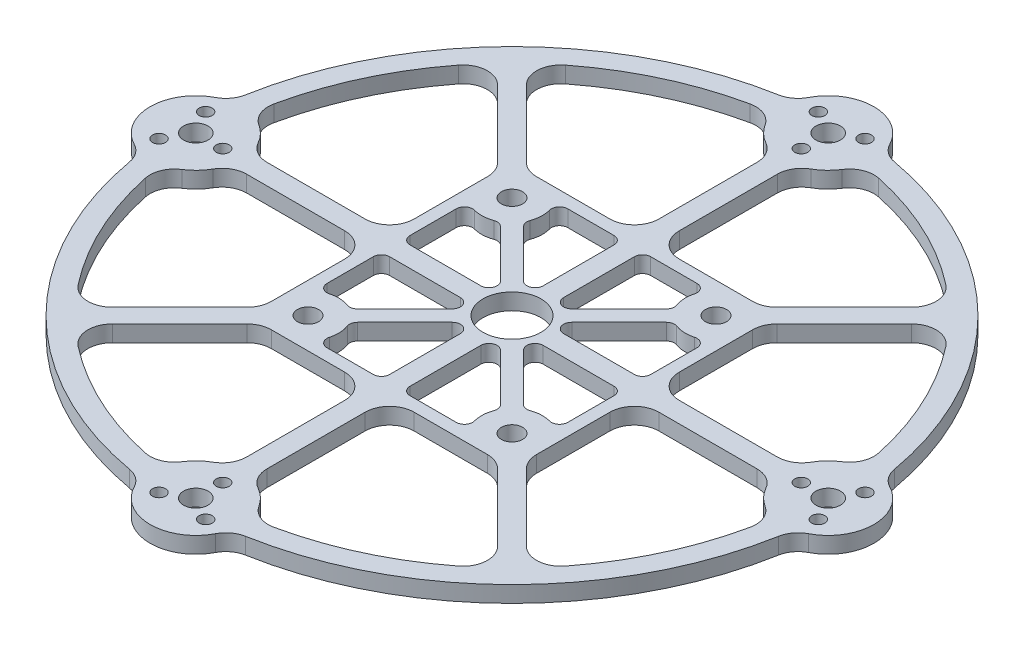
SolidWorks part; units mm, degrees
ref_plane "Front Plane" through (0, 0, 0) normal (0, 0, 1) x (1, 0, 0)
ref_plane "Top Plane" through (0, 0, 0) normal (0, 1, 0) x (1, 0, 0)
ref_plane "Right Plane" through (0, 0, 0) normal (1, 0, 0) x (0, 0, -1)
sketch "Sketch1" plane through (0, 0, 0) normal (0, 1, 0) x (1, 0, 0)
  line L1 (16.25, -16.25) -> (-16.25, -16.25)
  line L2 (16.25, -16.25) -> (16.25, 16.25)
  line L3 (16.25, 16.25) -> (-16.25, 16.25)
  line L4 (-16.25, -16.25) -> (-16.25, 16.25)
  line L5 (16.25, -16.25) -> (-16.25, 16.25) construction
  line L6 (16.25, 16.25) -> (-16.25, -16.25) construction
  point P0 (0, 0)
  dimension "D1" = 32.5
extrude "Boss-Extrude1" add sketch "Sketch1" along normal mid plane 2
sketch "Sketch5" plane through (0, 1, 0) normal (0, 1, 0) x (1, 0, 0)
  line L1 (12.5, -12.5) -> (-12.5, -12.5) construction
  line L2 (12.5, -12.5) -> (12.5, 12.5) construction
  line L3 (12.5, 12.5) -> (-12.5, 12.5) construction
  line L4 (-12.5, -12.5) -> (-12.5, 12.5) construction
  line L5 (12.5, -12.5) -> (-12.5, 12.5) construction
  line L6 (12.5, 12.5) -> (-12.5, -12.5) construction
  point P0 (0, 0)
  point P1 (-12.5, 12.5)
  point P2 (12.5, -12.5)
  point P3 (12.5, 12.5)
  point P4 (-12.5, -12.5)
  dimension "D1" = 25
hole_wizard "M2 Clearance Hole1" positions "Sketch5" profile "Sketch6" hole size "M2" standard "ISO"
sketch "Sketch6" plane through (-12.5, 1, 12.5) normal (1, 0, 0) x (0, 0, 1)
  line L0 (0, 0) -> (0, 2)
  line L1 (0, 2) -> (1.3, 2)
  line L2 (1.3, 2) -> (1.3, 0)
  line L5 (1.3, 0) -> (0, 0)
  line L11 (0, -6.35) -> (0, 107.95) construction
  dimension "Thru Hole Dia." = 2.6
  dimension "Thru Hole Depth" = 2
sketch "Sketch7" plane through (0, -1, 0) normal (0, -1, 0) x (1, 0, 0)
  line L0 (16.25, 16.25) -> (16.25, -16.25) construction
  line L1 (0, 0) -> (38.75, 0) construction
  line L2 (38.75, 0) -> (40.4, 2.8579) construction
  line L3 (38.75, 0) -> (35.45, 0) construction
  line L4 (38.75, 0) -> (40.4, -2.8579) construction
  line L5 (33.2913, 1.25) -> (16.25, 1.25)
  line L6 (16.25, 1.25) -> (16.25, -1.25)
  line L7 (16.25, 12.5) -> (16.25, -12.5)
  line L9 (16.25, -1.25) -> (33.2913, -1.25)
  circle A0 centre (38.75, 0) radius 22.5 construction
  circle A1 centre (38.75, 0) radius 3.3 construction
  circle A3 centre (35.45, 0) radius 0.8
  circle A5 centre (38.75, 0) radius 4.1 construction
  circle A6 centre (38.75, 0) radius 5.6
  circle A7 centre (40.4, 2.8579) radius 0.8
  circle A8 centre (40.4, -2.8579) radius 0.8
  circle A9 centre (40.4, 2.8579) radius 1.8 construction
  circle A10 centre (35.45, 0) radius 1.8 construction
  circle A11 centre (38.75, 0) radius 1.5
  dimension "D1" = 45
  dimension "D2" = 6.6
  dimension "D5" = 1.6
  dimension "D3" = 120
  dimension "D4" = 120
  dimension "D7" = 2.5
  dimension "D6" = 1.5
  dimension "D9" = 1
  dimension "D8" = 3
extrude "Boss-Extrude2" add sketch "Sketch7" against normal up to surface (2 mm away)
sketch "Sketch8" plane through (0, 0, 0) normal (0, 0, 1) x (1, 0, 0)
  line L0 (0, 0) -> (0, -50000) construction
pattern_circular "CirPattern1" count 4 every 90 about axis through (0, 0, 0) along (0, 1, 0) of "Boss-Extrude2"
sketch "Sketch13" plane through (0, -1, 0) normal (0, -1, 0) x (1, 0, 0)
  line L0 (0, -38.75) -> (-5.6, -38.75) construction
  arc A0 (-5.4559, -37.4877) -> (-37.4877, -5.4559) centre (0, 0) cw
  arc A1 (-1.25, -33.2913) -> (1.25, -33.2913) centre (0, -38.75) ccw construction
  arc A2 (-33.2913, 1.25) -> (-33.2913, -1.25) centre (-38.75, 0) ccw construction
  arc A3 (-40.0123, -5.4559) -> (-5.4559, -40.0123) centre (0, 0) ccw
  arc A4 (-5.4559, -40.0123) -> (-5.4559, -37.4877) centre (0, -38.75) cw
  arc A5 (-40.0123, -5.4559) -> (-37.4877, -5.4559) centre (-38.75, 0) ccw
  dimension "D1" = 2.5
extrude "Boss-Extrude3" add sketch "Sketch13" against normal up to surface (2 mm away) up to face at (-12.5, 1, -11.2)
pattern_circular "CirPattern3" count 4 every 90 about axis through (0, 0, 0) along (0, -1, 0) of "Boss-Extrude3"
sketch "Sketch14" plane through (0, 1, 0) normal (0, 1, 0) x (1, 0, 0)
  line L0 (-16.25, -1.25) -> (-16.25, -16.25) construction
  line L4 (-12.5, -12.5) -> (0, 0) construction
  line L5 (-14.75, -1.25) -> (-14.75, -9.5)
  line L6 (-14.75, -14.75) -> (-1.25, -14.75)
  line L7 (-14.75, -1.25) -> (-14.75, -14.75)
  line L8 (-14.75, -14.75) -> (-1.25, -14.75) construction
  line L9 (-14.75, -1.25) -> (-14.75, -14.75) construction
  line L10 (-11.7929, -13.2071) -> (0.7071, -0.7071) construction
  line L11 (-13.2071, -11.7929) -> (-0.7071, 0.7071) construction
  line L12 (-14.75, -1.25) -> (-2.6642, -1.25)
  line L13 (-2.6642, -1.25) -> (-10.6515, -9.2373)
  line L14 (-1.25, -14.75) -> (-1.25, -2.6642)
  line L15 (-1.25, -2.6642) -> (-9.2373, -10.6515)
  line L16 (-1.25, -14.75) -> (-9.5, -14.75)
  circle A0 centre (-12.5, -12.5) radius 3.75 construction
  arc A2 (-14.75, -9.5) -> (-10.6515, -9.2373) centre (-12.5, -12.5) cw
  arc A3 (-9.2373, -10.6515) -> (-9.5, -14.75) centre (-12.5, -12.5) cw
  dimension "D1" = 1.5
  dimension "D2" = 1
  dimension "D3" = 1
extrude "Cut-Extrude2" cut sketch "Sketch14" against normal through all both and the other way through all
pattern_circular "CirPattern4" count 4 every 90 about axis through (0, 0, 0) along (0, 1, 0) of "Cut-Extrude2"
fillet "Fillet2" radius 1 32 edges at (1.25, 0, 14.75) (1.25, 0, 2.6642) (14.75, 0, 1.25) (2.6642, 0, 1.25) (14.75, 0, -1.25) (1.25, 0, -2.6642) (2.6642, 0, -1.25) (1.25, 0, -14.75) (-2.6642, 0, -1.25) (-1.25, 0, 14.75) (-14.75, 0, 1.25) (-1.25, 0, 2.6642) (-2.6642, 0, 1.25) (-1.25, 0, -14.75) (-14.75, 0, -1.25) (-1.25, 0, -2.6642)
sketch "Sketch15" plane through (0, 1, 0) normal (0, 1, 0) x (1, 0, 0)
  circle A0 centre (0, 0) radius 4.5545 construction
  arc A1 (-2.9571, 4.3713) -> (-1.25, 5.0784) centre (-2.25, 5.0784) ccw construction
  circle A2 centre (0, 0) radius 3.5545
  dimension "D1" = 1
extrude "Cut-Extrude3" cut sketch "Sketch15" against normal through all both and the other way through all
sketch "Sketch16" plane through (0, -1, 0) normal (0, -1, 0) x (1, 0, 0)
  line L0 (14.4822, -16.25) -> (25.8886, -27.6563)
  line L1 (16.25, -16.25) -> (1.25, -16.25) construction
  line L3 (16.25, -14.4822) -> (27.6563, -25.8886)
  line L4 (16.25, -1.25) -> (16.25, -16.25) construction
  line L5 (14.4822, -16.25) -> (16.25, -14.4822) construction
  line L6 (16.25, -14.4822) -> (16.25, -16.25)
  line L7 (16.25, -16.25) -> (14.4822, -16.25)
  arc A0 (5.4559, -37.4877) -> (37.4877, -5.4559) centre (0, 0) ccw construction
  arc A1 (27.6563, -25.8886) -> (25.8886, -27.6563) centre (0, 0) cw
  point P13 (0, 0)
  point P14 (0, 0)
  dimension "D1" = 2.5
extrude "Boss-Extrude4" add sketch "Sketch16" against normal up to surface (2 mm away) up to face at (0, 1, 3.5545)
pattern_circular "CirPattern5" count 4 over 360 about axis through (0, 0, 0) along (0, 1, 0) of "Boss-Extrude4"
fillet "Fillet1" radius 3 48 edges at (16.25, 0, -1.25) (37.4877, 0, 5.4559) (33.2913, 0, 1.25) (40.0123, 0, 5.4559) (40.0123, 0, -5.4559) (33.2913, 0, -1.25) (37.4877, 0, -5.4559) (16.25, 0, -14.4822) (27.6563, 0, -25.8886) (25.8886, 0, -27.6563) (14.4822, 0, -16.25) (5.4559, 0, 40.0123) (-5.4559, 0, 40.0123) (-40.0123, 0, 5.4559) (-40.0123, 0, -5.4559) (-5.4559, 0, -40.0123) (5.4559, 0, -40.0123) (1.25, 0, 33.2913) (5.4559, 0, 37.4877) (1.25, 0, -16.25) (-37.4877, 0, -5.4559) (-33.2913, 0, -1.25) (-27.6563, 0, -25.8886) (-1.25, 0, 16.25) (25.8886, 0, 27.6563) (14.4822, 0, 16.25) (-16.25, 0, 1.25) (-16.25, 0, -14.4822) (-5.4559, 0, -37.4877) (-1.25, 0, -33.2913) (27.6563, 0, 25.8886) (-5.4559, 0, 37.4877) (-1.25, 0, 33.2913) (-27.6563, 0, 25.8886) (-16.25, 0, 14.4822) (-16.25, 0, -1.25) (-14.4822, 0, -16.25) (-1.25, 0, -16.25) (16.25, 0, 1.25) (16.25, 0, 14.4822) (1.25, 0, 16.25) (-14.4822, 0, 16.25) (-25.8886, 0, 27.6563) (-37.4877, 0, 5.4559) (-33.2913, 0, 1.25) (-25.8886, 0, -27.6563) (5.4559, 0, -37.4877) (1.25, 0, -33.2913)
